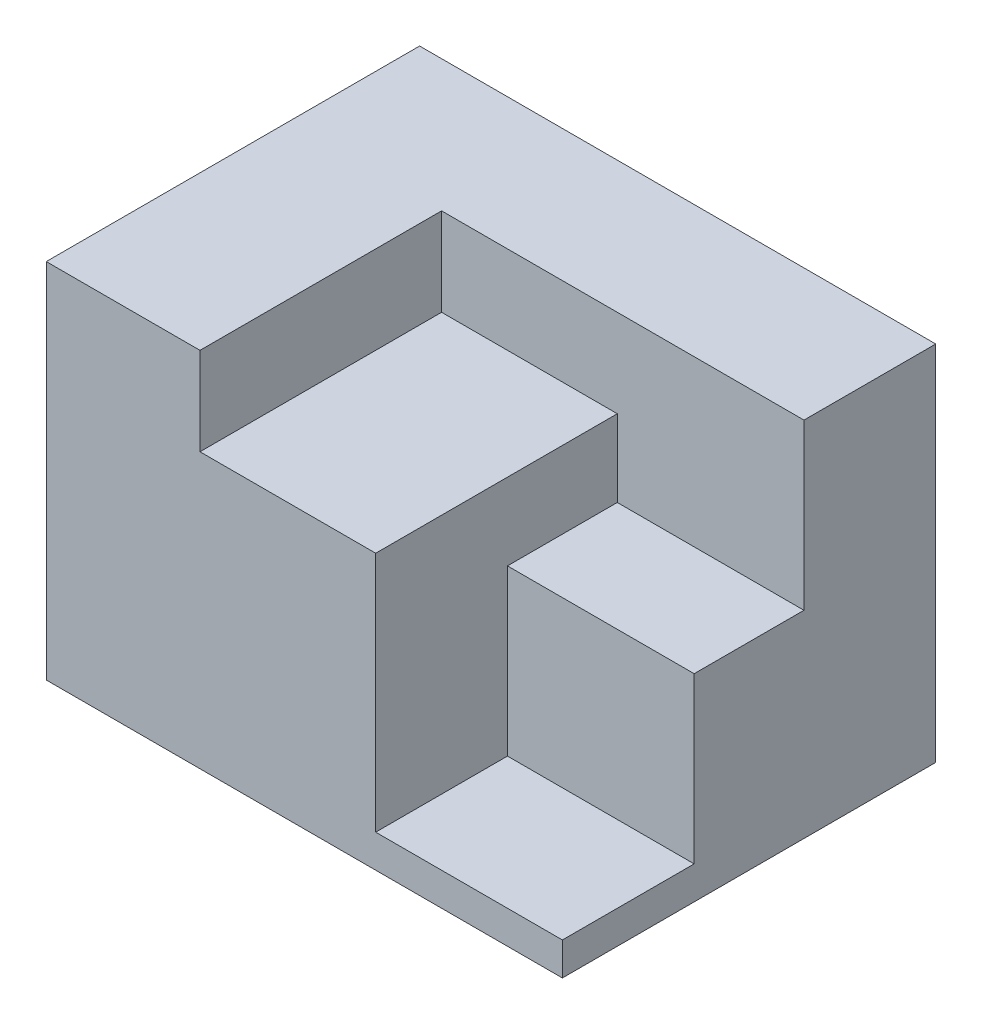
SolidWorks part; units mm, degrees
ref_plane "Front Plane" through (0, 0, 0) normal (0, 0, 1) x (1, 0, 0)
ref_plane "Top Plane" through (0, 0, 0) normal (0, 1, 0) x (1, 0, 0)
ref_plane "Right Plane" through (0, 0, 0) normal (1, 0, 0) x (0, 0, -1)
sketch "Sketch1" plane through (0, 0, 0) normal (0, 0, 1) x (1, 0, 0)
  line L1 (-20.8186, 17.6972) -> (26.1814, 17.6972)
  line L2 (-20.8186, 17.6972) -> (-20.8186, -15.3028)
  line L3 (-20.8186, -15.3028) -> (26.1814, -15.3028)
  line L4 (26.1814, 17.6972) -> (26.1814, -15.3028)
  dimension "D1" = 47
  dimension "D2" = 33
extrude "Boss-Extrude1" add sketch "Sketch1" along normal blind 34
sketch "Sketch2" plane through (0, 0, 34) normal (0, 0, 1) x (1, 0, 0)
  line L0 (26.1814, 17.6972) -> (-20.8186, 17.6972) construction
  line L1 (-6.8186, 17.6972) -> (26.1814, 17.6972)
  line L2 (-6.8186, 17.6972) -> (-6.8186, 9.6972)
  line L3 (-6.8186, 9.6972) -> (26.1814, 9.6972)
  line L4 (26.1814, 17.6972) -> (26.1814, 9.6972)
  line L5 (26.1814, -15.3028) -> (26.1814, 17.6972) construction
  dimension "D1" = 14
  dimension "D2" = 8
extrude "Cut-Extrude1" cut sketch "Sketch2" against normal blind 22
sketch "Sketch3" plane through (26.1814, 0, 0) normal (1, 0, 0) x (0, 0, -1)
  line L0 (-34, -15.3028) -> (-34, 9.6972) construction
  line L1 (-12, 9.6972) -> (-34, 9.6972)
  line L2 (-12, 9.6972) -> (-12, 2.6972)
  line L3 (-12, 2.6972) -> (-34, 2.6972)
  line L4 (-34, 9.6972) -> (-34, 2.6972)
  line L5 (-34, -15.3028) -> (0, -15.3028) construction
  line L7 (-34, 2.6972) -> (-34, -12.3028)
  line L8 (-34, -12.3028) -> (-22, -12.3028)
  line L9 (-22, 2.6972) -> (-22, -12.3028)
  line M7 (-12, 9.6972) -> (-34, 9.6972)
  line M8 (-34, 9.6972) -> (-34, -15.3028)
  dimension "D1" = 7
  dimension "D2" = 12
  dimension "D3" = 3
extrude "Cut-Extrude2" cut sketch "Sketch3" against normal blind 17 contours L9 L3 L8 M8 | L3 L2 M7 M8
